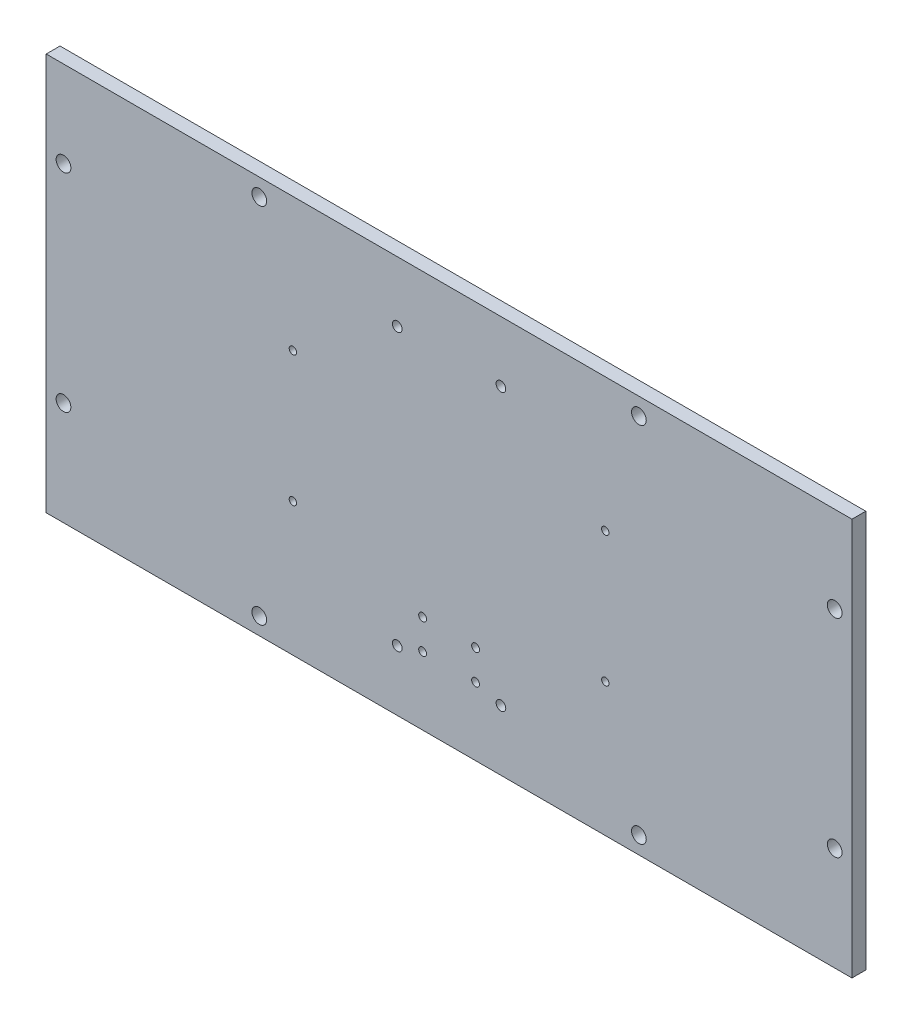
SolidWorks part; units mm, degrees
ref_plane "Front Plane" through (0, 0, 0) normal (0, 0, 1) x (1, 0, 0)
ref_plane "Top Plane" through (0, 0, 0) normal (0, 1, 0) x (1, 0, 0)
ref_plane "Right Plane" through (0, 0, 0) normal (1, 0, 0) x (0, 0, -1)
sketch "Sketch2" plane through (0, 0, 0) normal (0, 0, 1) x (1, 0, 0)
  line L0 (0, 90) -> (0, -90) construction
  line L1 (-22.5, 56.25) -> (-22.5, -3.75) construction
  line L2 (22.5, 56.25) -> (22.5, -3.75) construction
  line L3 (-67.818, 24.571) -> (-67.818, -32.071) construction
  line L4 (67.818, 24.571) -> (67.818, -32.071) construction
  line L5 (-11.5, -47.5) -> (11.5, -47.5) construction
  line L6 (11.5, -47.5) -> (11.5, -60.5) construction
  line L7 (11.5, -60.5) -> (-11.5, -60.5) construction
  line L8 (182.4, -90) -> (182.4, 90) construction
  line L9 (182.4, 90) -> (-182.4, 90) construction
  line L10 (-182.4, 90) -> (-182.4, -90) construction
  line L11 (-174.9, -90) -> (174.9, -90)
  line L12 (-11.5, -60.5) -> (-11.5, -47.5) construction
  line L13 (-11.5, -54) -> (11.5, -54) construction
  line L14 (82.4, -67.5) -> (-82.4, -67.5) construction
  line L15 (-67.818, -3.75) -> (67.818, -3.75) construction
  line L16 (-34.359, 60) -> (-9.8715, 60) construction
  line L17 (-174.9, 82.5) -> (174.9, 82.5)
  line L18 (-174.9, 82.5) -> (-174.9, -90)
  line L19 (174.9, 82.5) -> (174.9, -90)
  line L20 (-174.9, -90) -> (-182.4, -90) construction
  line L21 (174.9, -90) -> (182.4, -90) construction
  circle A0 centre (-82.4, 75) radius 3.2
  circle A1 centre (82.4, 75) radius 3.2
  circle A2 centre (22.5, -3.75) radius 2.1 construction
  circle A3 centre (-67.818, 24.571) radius 1.6
  circle A4 centre (-167.4, -45) radius 3.2
  circle A5 centre (167.4, -45) radius 3.2
  circle A6 centre (22.5, -63.75) radius 2.1
  circle A7 centre (22.5, 56.25) radius 2.1
  circle A8 centre (-67.818, -32.071) radius 1.6
  circle A9 centre (67.818, -32.071) radius 1.6
  circle A10 centre (67.818, 24.571) radius 1.6
  circle A11 centre (-22.5, 56.25) radius 2.1
  circle A12 centre (-22.5, -3.75) radius 2.1 construction
  circle A13 centre (-22.5, -63.75) radius 2.1
  circle A14 centre (-11.5, -47.5) radius 1.7
  circle A15 centre (11.5, -47.5) radius 1.7
  circle A16 centre (-167.4, 45) radius 3.2
  circle A17 centre (167.4, 45) radius 3.2
  circle A18 centre (-11.5, -60.5) radius 1.7
  circle A19 centre (11.5, -60.5) radius 1.7
  circle A20 centre (-82.4, -82.5) radius 3.2
  circle A21 centre (82.4, -82.5) radius 3.2
  dimension "D10" = 6.4
  dimension "D7" = 15
  dimension "D22" = 4.2
  dimension "D24" = 3.2
  dimension "D33" = 3.4
  dimension "D35" = 7.5
  dimension "D2" = 15
  dimension "D1" = 364.8
  dimension "D3" = 15
  dimension "D4" = 120
  dimension "D5" = 60
  dimension "D6" = 15
  dimension "D8" = 45
  dimension "D9" = 90
  dimension "D11" = 15
  dimension "D12" = 100
  dimension "D13" = 100
  dimension "D14" = 15
  dimension "D15" = 45
  dimension "D16" = 90
  dimension "D17" = 45
  dimension "D18" = 90
  dimension "D19" = 45
  dimension "D20" = 45
  dimension "D21" = 60
  dimension "D23" = 3.75
  dimension "D25" = 56.642
  dimension "D26" = 56.642
  dimension "D27" = 135.636
  dimension "D28" = 180
  dimension "D29" = 65.429
  dimension "D30" = 15
  dimension "D31" = 23
  dimension "D32" = 13
  dimension "D34" = 36
  dimension "D36" = 7.5
  dimension "D37" = 100
  dimension "D38" = 100
  dimension "D39" = 15
  dimension "D40" = 7
  dimension "D41" = 157.5
  dimension "D42" = 30
  dimension "D43" = 3.75
  dimension "D44" = 7.5
  dimension "D45" = 7.5
  dimension "D46" = 7.5
extrude "Boss-Extrude1" add sketch "Sketch2" along normal blind 6
